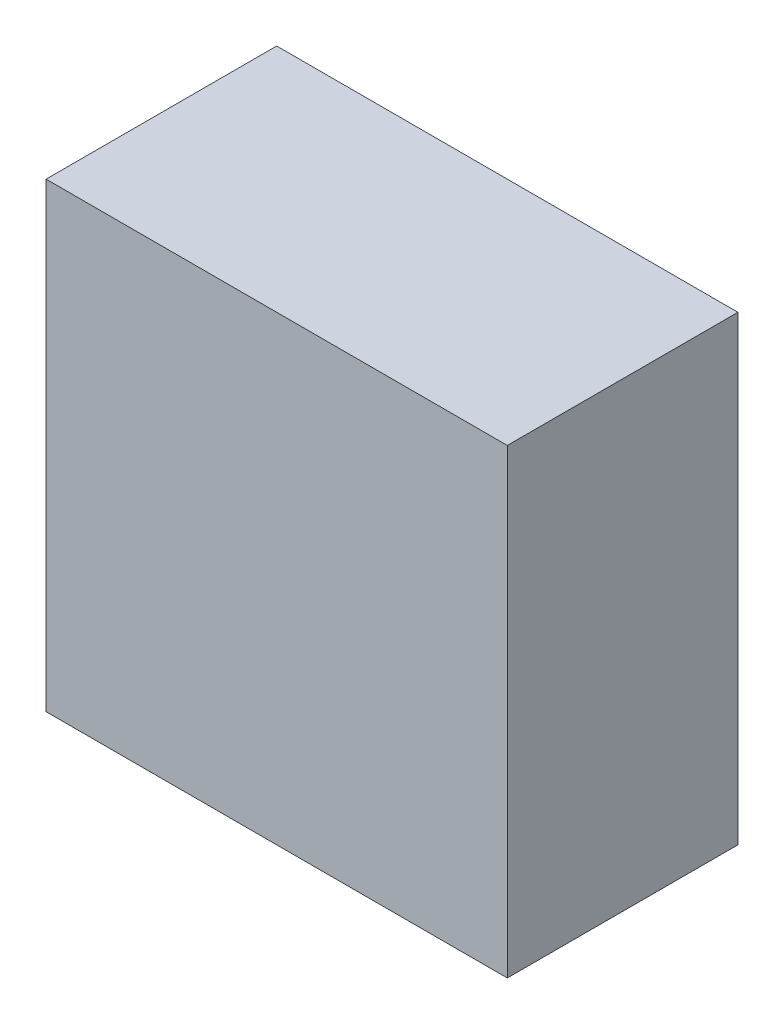
SolidWorks part; units mm, degrees
ref_plane "Face" through (0, 0, 0) normal (0, 0, 1) x (1, 0, 0)
ref_plane "Dessus" through (0, 0, 0) normal (0, 1, 0) x (1, 0, 0)
ref_plane "Droite" through (0, 0, 0) normal (1, 0, 0) x (0, 0, -1)
sketch "Esquisse1" plane through (0, 0, 0) normal (0, 0, 1) x (1, 0, 0)
  line L0 (50.0447, 6.9677) -> (50.0447, -13.0323)
  line L1 (50.0447, -13.0323) -> (70.0447, -13.0323)
  line L3 (50.0447, 6.9677) -> (70.0447, 6.9677)
  line L4 (70.0447, -13.0323) -> (70.0447, 6.9677)
  dimension "D1" = 20
  dimension "D2" = 20
extrude "Base-Extrusion" add sketch "Esquisse1" along normal blind 10
